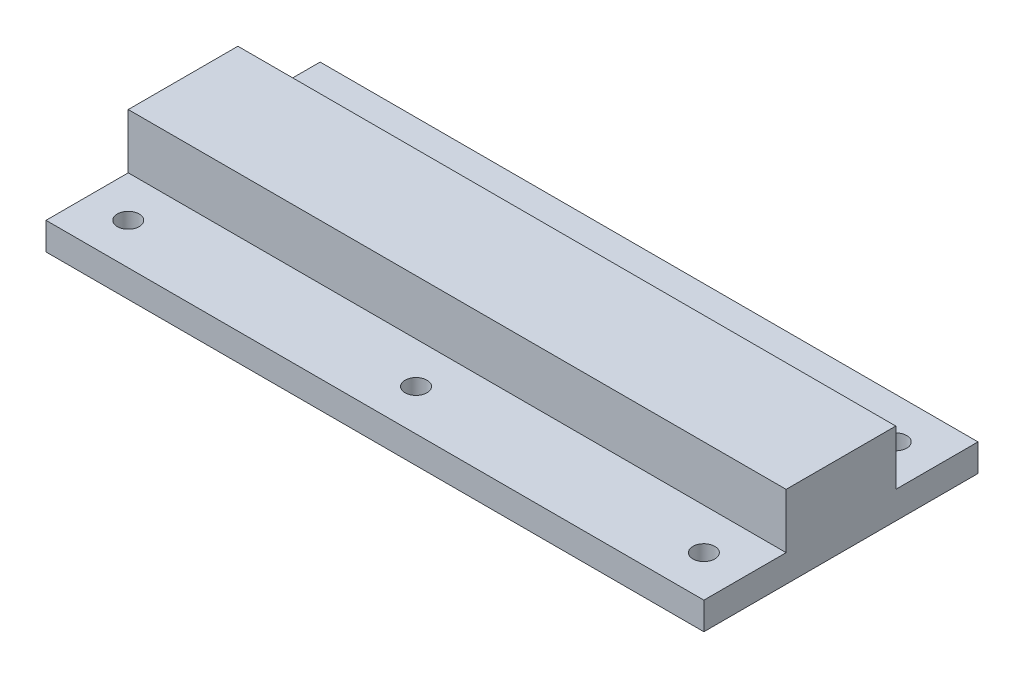
SolidWorks part; units mm, degrees
ref_plane "Front Plane" through (0, 0, 0) normal (0, 0, 1) x (1, 0, 0)
ref_plane "Top Plane" through (0, 0, 0) normal (0, 1, 0) x (1, 0, 0)
ref_plane "Right Plane" through (0, 0, 0) normal (1, 0, 0) x (0, 0, -1)
sketch "Sketch2" plane through (0, 0, 0) normal (0, 1, 0) x (1, 0, 0)
  line L0 (-46.8981, 34.5466) -> (-46.8981, -15.4534)
  line L1 (-46.8981, -15.4534) -> (73.1019, -15.4534)
  line L2 (73.1019, -15.4534) -> (73.1019, 34.5466)
  line L3 (73.1019, 34.5466) -> (-46.8981, 34.5466)
  dimension "D1" = 120
  dimension "D2" = 50
extrude "Boss-Extrude1" add sketch "Sketch2" along normal blind 15
sketch "Sketch3" plane through (0, 0, 0) normal (0, 1, 0) x (1, 0, 0)
  line L0 (74.3548, 9.5466) -> (-56.2815, 9.5466) construction
  line L1 (63.1019, 9.5466) -> (63.1019, 17.0466)
  line L2 (63.1019, 17.0466) -> (3.1019, 17.0466)
  line L3 (3.1019, 17.0466) -> (3.1019, 19.5466)
  line L4 (3.1019, 19.5466) -> (-36.8981, 19.5466)
  line L5 (-36.8981, 19.5466) -> (-36.8981, 9.5466)
  line L6 (-36.8981, 9.5466) -> (63.1019, 9.5466)
  line L7 (73.1019, -15.4534) -> (73.1019, 34.5466) construction
  line L9 (-46.8981, -15.4534) -> (73.1019, -15.4534) construction
  dimension "D1" = 60
  dimension "D2" = 40
  dimension "D3" = 10
  dimension "D4" = 25
  dimension "D5" = 10
  dimension "D6" = 7.5
sketch "Skizze7" plane through (-46.8981, 0, 0) normal (-1, 0, 0) x (0, 0, 1)
  line L1 (-34.5466, 0) -> (15.4534, 0) construction
  line L3 (-9.5466, -6.0172) -> (-9.5466, 6.0172) construction
  line L4 (15.4534, 15) -> (15.4534, 0) construction
  line L5 (-34.5466, 15) -> (-34.5466, 0) construction
  circle A0 centre (-9.5466, 2.5) radius 1.5
  dimension "D1" = 3
  dimension "D2" = 2.5
extrude "Schnitt-Linear austragen6" cut sketch "Skizze7" against normal blind 10
revolve "Schnitt-Rotation1" cut sketch "Sketch3" angle 360 about L0
sketch "Skizze10" plane through (0, 0, 0) normal (0, -1, 0) x (1, 0, 0)
  line L0 (63.1019, -17.0466) -> (3.1019, -17.0466) construction
  line L1 (53.1019, -17.0466) -> (40.6019, -17.0466)
  line L2 (53.1019, -17.0466) -> (53.1019, -15.5466)
  line L3 (53.1019, -15.5466) -> (40.6019, -15.5466)
  line L4 (40.6019, -17.0466) -> (40.6019, -15.5466)
  line L5 (63.1019, -2.0466) -> (63.1019, -17.0466) construction
  line L10 (85.7448, -9.5466) -> (-66.8579, -9.5466) construction
  line L11 (-46.8981, 15.4534) -> (73.1019, 15.4534) construction
  line L12 (73.1019, -34.5466) -> (-46.8981, -34.5466) construction
  dimension "D1" = 10
  dimension "D2" = 12.5
  dimension "D5" = 1.5
revolve "Rotation3" add sketch "Skizze10" angle 180 about L10
sketch "Skizze11" plane through (0, 0, 0) normal (0, -1, 0) x (1, 0, 0)
  line L0 (40.6019, -17.0466) -> (3.1019, -17.0466) construction
  line L1 (28.1019, -17.0466) -> (15.6019, -17.0466)
  line L2 (28.1019, -17.0466) -> (28.1019, -15.5466)
  line L3 (28.1019, -15.5466) -> (15.6019, -15.5466)
  line L4 (15.6019, -17.0466) -> (15.6019, -15.5466)
  line L5 (53.1019, -15.5466) -> (40.6019, -15.5466) construction
  line L6 (40.6019, -15.5466) -> (40.6019, -17.0466) construction
  line L7 (95.0378, -9.5466) -> (-94.5432, -9.5466) construction
  line L8 (-46.8981, 15.4534) -> (73.1019, 15.4534) construction
  line L9 (73.1019, -34.5466) -> (-46.8981, -34.5466) construction
  point P10 (40.6019, -16.2966)
  dimension "D1" = 12.5
  dimension "D2" = 12.5
revolve "Rotation4" add sketch "Skizze11" angle 180 about L7
sketch "Skizze12" plane through (0, 0, 0) normal (0, -1, 0) x (1, 0, 0)
  line L0 (73.1019, 15.4534) -> (73.1019, -34.5466) construction
  line L1 (-46.8981, -34.5466) -> (-46.8981, 15.4534) construction
  line L3 (-46.8981, 15.4534) -> (73.1019, 15.4534) construction
  circle A0 centre (-39.3981, 7.9534) radius 2
  circle A1 centre (13.1019, 7.9534) radius 2
  circle A2 centre (65.6019, 7.9534) radius 2
  dimension "D3" = 4
  dimension "D2" = 7.5
  dimension "D4" = 7.5
  dimension "D5" = 7.5
  dimension "D1" = 3
ref_plane "Ebene6" through (0, 0, -9.5466) normal (0, 0, 1) x (1, 0, 0)
extrude "Schnitt-Linear austragen7" cut sketch "Skizze12" against normal through all
mirror "Spiegeln1" about plane through (0, 0, -9.5466) normal (0, 0, 1) of "Schnitt-Linear austragen7"
sketch "Skizze13" plane through (-46.8981, 0, 0) normal (-1, 0, 0) x (0, 0, 1)
  line L0 (-34.5466, 0) -> (15.4534, 0) construction
  line L1 (15.4534, 15) -> (0.4534, 15)
  line L2 (15.4534, 15) -> (15.4534, 5)
  line L3 (15.4534, 5) -> (0.4534, 5)
  line L4 (0.4534, 15) -> (0.4534, 5)
  line L5 (-34.5466, 0) -> (15.4534, 0) construction
  line L6 (-34.5466, 15) -> (-19.5466, 15)
  line L7 (-34.5466, 15) -> (-34.5466, 5)
  line L8 (-34.5466, 5) -> (-19.5466, 5)
  line L9 (-19.5466, 15) -> (-19.5466, 5)
  dimension "D1" = 15
  dimension "D2" = 5
  dimension "D3" = 15
  dimension "D4" = 5
extrude "Schnitt-Linear austragen8" cut sketch "Skizze13" against normal through all contours L2 L1 L4 L3 | L7 L6 L9 L8
